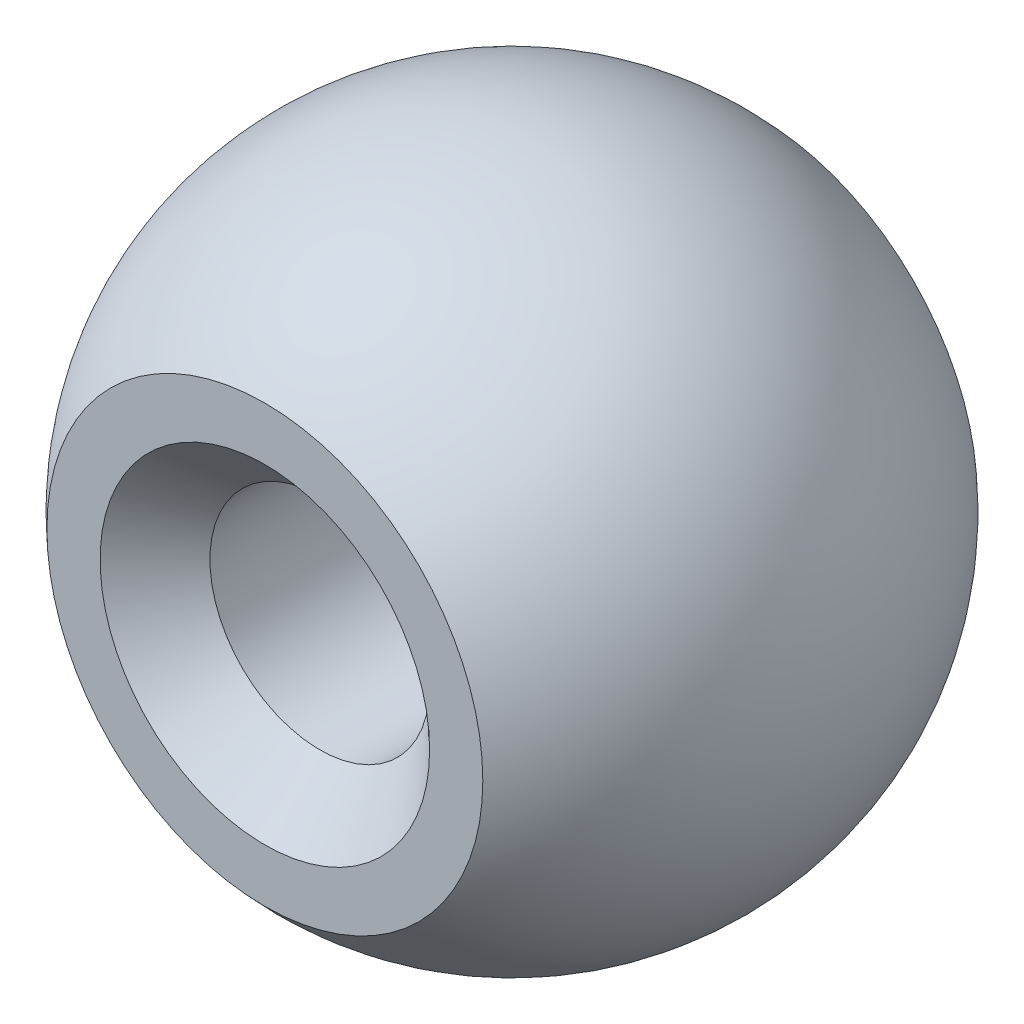
SolidWorks part; units mm, degrees
ref_plane "Front Plane" through (0, 0, 0) normal (0, 0, 1) x (1, 0, 0)
ref_plane "Top Plane" through (0, 0, 0) normal (0, 1, 0) x (1, 0, 0)
ref_plane "Right Plane" through (0, 0, 0) normal (1, 0, 0) x (0, 0, -1)
sketch "Sketch1" plane through (0, 0, 0) normal (0, 1, 0) x (1, 0, 0)
  line L0 (0, 9.7176) -> (0, -8.2276) construction
  line L1 (0, 0) -> (5.4184, -2.577) construction
  line L2 (0, 4.5) -> (3.9686, 4.5)
  line L6 (0, -4.5) -> (0, 4.5)
  line L8 (0, 0) -> (5.4184, 2.577) construction
  line L9 (0, -4.5) -> (3.9686, -4.5)
  arc A1 (3.9686, -4.5) -> (3.9686, 4.5) centre (0, 0) ccw
  dimension "D1" = 6
  dimension "D2" = 9
revolve "Revolve1" add sketch "Sketch1" angle 360 about L6
hole_wizard "CSK for M2 Cross Countersunk Head Screw1" positions "Sketch2" profile "Sketch3" countersink size "M2" standard "AS" end condition up to next
sketch "Sketch2" plane through (0, 0, 4.5) normal (0, 0, 1) x (1, 0, 0)
  point P0 (0, 0)
sketch "Sketch3" plane through (0, 0, 4.5) normal (1, 0, 0) x (0, -1, 0)
  line L0 (0, 0) -> (0, 9)
  line L1 (0, 9) -> (2, 9)
  line L2 (2, 9) -> (2, 1)
  line L3 (2, 1) -> (3, 0)
  line L5 (3, 0) -> (0, 0)
  line L6 (-2, 1) -> (-3, 0) construction
  line L11 (0, -6.35) -> (0, 107.95) construction
  dimension "Thru Hole Dia." = 4
  dimension "Thru Hole Depth" = 9
  dimension "Near C'Sink Dia." = 6
  dimension "Near C'Sink Angle" = 90
